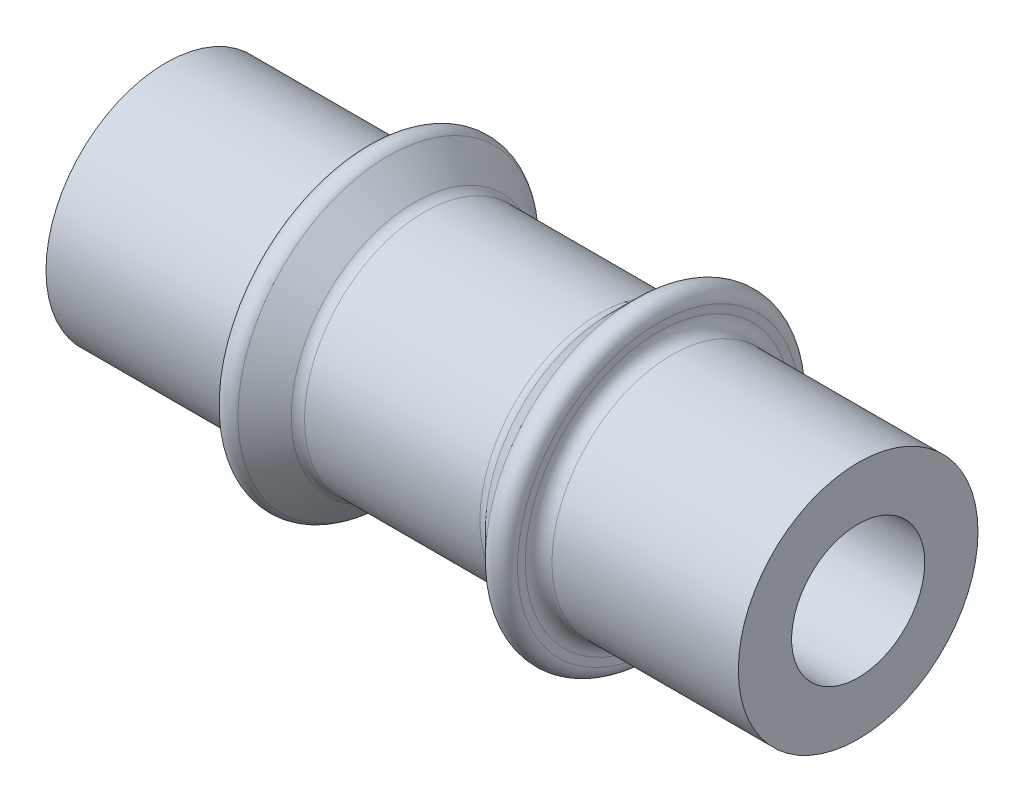
SolidWorks part; units mm, degrees
material "ABS"
ref_plane "Front Plane" through (0, 0, 0) normal (0, 0, 1) x (1, 0, 0)
ref_plane "Top Plane" through (0, 0, 0) normal (0, 1, 0) x (1, 0, 0)
ref_plane "Right Plane" through (0, 0, 0) normal (1, 0, 0) x (0, 0, -1)
sketch "Sketch1" plane through (0, 0, 0) normal (0, 0, 1) x (1, 0, 0)
  line L0 (0, 0) -> (-26, 0) construction
  line L1 (-26, 2.5) -> (0, 2.5)
  line L2 (-26, 2.5) -> (-26, 4.5)
  line L3 (-26, 4.5) -> (-19, 4.5)
  line L4 (-18.5, 5) -> (-18.5, 5.2929)
  line L5 (-17.6464, 5.6464) -> (-16.6464, 4.6464)
  line L6 (-16.2929, 4.5) -> (-9.7071, 4.5)
  line L7 (-9.3536, 4.6464) -> (-8.3536, 5.6464)
  line L8 (-7.5, 5.2929) -> (-7.5, 5)
  line L9 (-7, 4.5) -> (0, 4.5)
  line L10 (0, 4.5) -> (0, 2.5)
  arc A0 (-7.5, 5) -> (-7, 4.5) centre (-7, 5) ccw
  arc A1 (-8.3536, 5.6464) -> (-7.5, 5.2929) centre (-8, 5.2929) cw
  arc A2 (-9.7071, 4.5) -> (-9.3536, 4.6464) centre (-9.7071, 5) ccw
  arc A3 (-19, 4.5) -> (-18.5, 5) centre (-19, 5) ccw
  arc A4 (-16.6464, 4.6464) -> (-16.2929, 4.5) centre (-16.2929, 5) ccw
  arc A5 (-18.5, 5.2929) -> (-17.6464, 5.6464) centre (-18, 5.2929) cw
  point P18 (-7.5, 4.5)
  point P21 (-7.5, 6.5)
  point P24 (-9.5, 4.5)
  point P27 (-18.5, 4.5)
  point P30 (-16.5, 4.5)
  point P33 (-18.5, 6.5)
  dimension "D10" = 0.5
  dimension "D1" = 26
  dimension "D2" = 2.5
  dimension "D3" = 2
  dimension "D4" = 7.5
  dimension "D5" = 7.5
  dimension "D6" = 2
  dimension "D7" = 2
  dimension "D8" = 2
  dimension "D9" = 2
revolve "Revolve1" add sketch "Sketch1" angle 360 about L0
